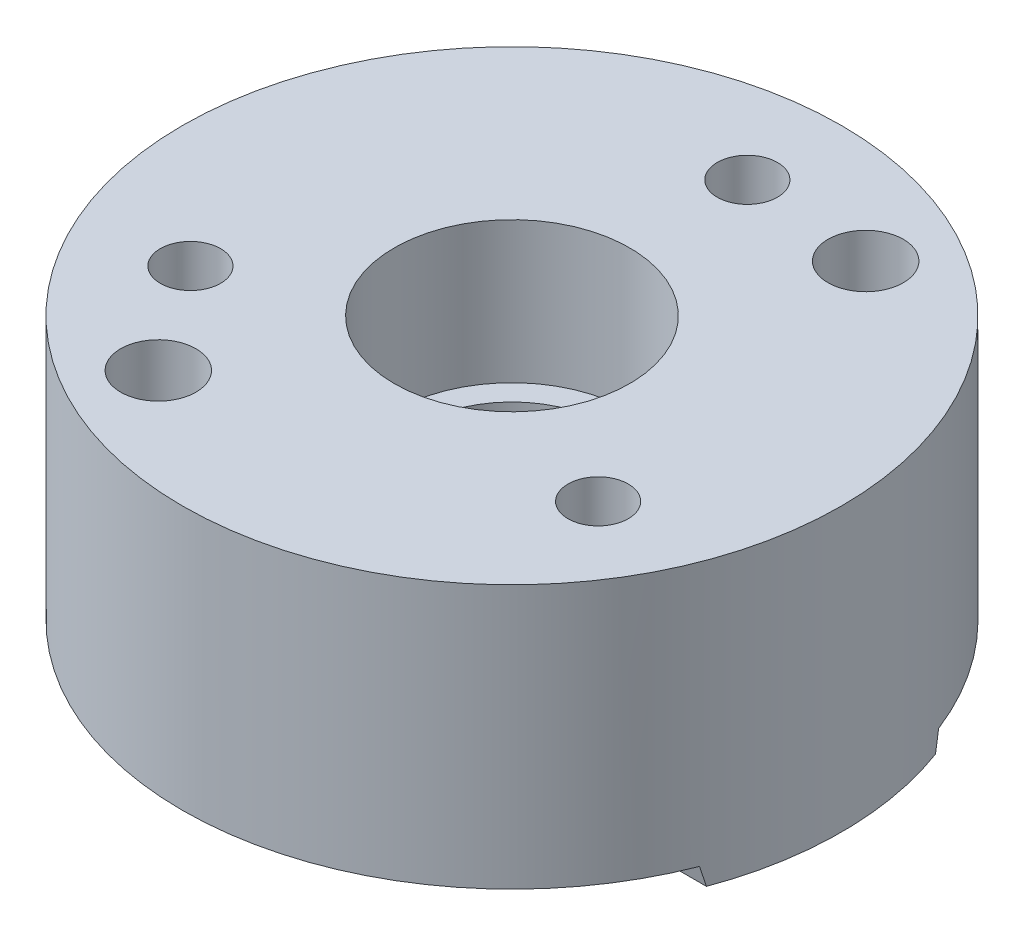
SolidWorks part; units mm, degrees
material "K110"
ref_plane "Front Plane" through (0, 0, 0) normal (0, 0, 1) x (1, 0, 0)
ref_plane "Top Plane" through (0, 0, 0) normal (0, 1, 0) x (1, 0, 0)
ref_plane "Right Plane" through (0, 0, 0) normal (1, 0, 0) x (0, 0, -1)
sketch "Sketch1" plane through (0, 0, 0) normal (0, 1, 0) x (1, 0, 0)
  circle A0 centre (0, 0) radius 35
  circle A1 centre (0, 0) radius 10
  dimension "D1" = 20
  dimension "D2" = 70
extrude "Boss-Extrude1" add sketch "Sketch1" against normal blind 30
sketch "Sketch4" plane through (0, 0, 0) normal (0, 1, 0) x (1, 0, 0)
  circle A0 centre (0, 0) radius 12.5
  dimension "D1" = 25
extrude "Cut-Extrude2" cut sketch "Sketch4" against normal blind 15
hole_wizard "CBORE for M6 Hex Socket Head Cap Screw1" positions "Sketch15" profile "Sketch8" counterbore size "M6" standard "ISO" end condition through all
sketch "Sketch15" plane through (0, -30, 0) normal (0, -1, 0) x (-1, 0, 0)
  line L0 (0, 25) -> (0, 0) construction
  line L1 (0, 0) -> (-21.6506, -12.5) construction
  line L3 (0, 0) -> (21.6506, -12.5) construction
  circle A0 centre (0, 0) radius 25 construction
  point P0 (0, 25)
  point P2 (21.6506, -12.5)
  point P4 (-21.6506, -12.5)
  dimension "D1" = 50
  dimension "D2" = 120
  dimension "D3" = 120
sketch "Sketch8" plane through (0, -30, -25) normal (1, 0, 0) x (0, 0, -1)
  line L0 (0, 0) -> (0, 30)
  line L1 (0, 30) -> (3.2, 30)
  line L3 (3.2, 30) -> (3.2, 8.4)
  line L4 (3.2, 8.4) -> (5.5, 8.4)
  line L5 (5.5, 8.4) -> (5.5, 0)
  line L7 (5.5, 0) -> (0, 0)
  line L11 (0, -6.35) -> (0, 107.95) construction
  dimension "Thru Hole Dia." = 6.4
  dimension "Thru Hole Depth" = 30
  dimension "C'Bore Dia." = 11
  dimension "C'Bore Depth" = 8.4
hole_wizard "Ø8.0mm Dowel Hole1" positions "Sketch17" profile "Sketch12" hole size "Ø8.0" standard "ISO" end condition through all
sketch "Sketch17" plane through (0, -30, 0) normal (0, -1, 0) x (-1, 0, 0)
  line L0 (-13.75, 23.8157) -> (13.75, -23.8157) construction
  line L1 (0, 35) -> (0, -35) construction
  circle A0 centre (0, 0) radius 27.5 construction
  circle A1 centre (0, 0) radius 35 construction
  point P0 (13.75, -23.8157)
  point P2 (-13.75, 23.8157)
  point P26 (0, 0)
  dimension "D1" = 55
  dimension "D2" = 30
sketch "Sketch12" plane through (-13.75, -30, 23.8157) normal (1, 0, 0) x (0, 0, -1)
  line L0 (0, 0) -> (0, 30)
  line L1 (0, 30) -> (4, 30)
  line L2 (4, 30) -> (4, 0)
  line L5 (4, 0) -> (0, 0)
  line L11 (0, -6.35) -> (0, 107.95) construction
  dimension "Thru Hole Dia." = 8
  dimension "Thru Hole Depth" = 30
sketch "Sketch14" plane through (0, -30, 0) normal (0, -1, 0) x (1, 0, 0)
  line L0 (-58.6405, -12.7) -> (-12.0399, -12.7) construction
  line L1 (-35, 12.7) -> (35, 12.7)
  line L2 (-35, 12.7) -> (-35, -12.7)
  line L3 (-35, -12.7) -> (35, -12.7)
  line L4 (35, 12.7) -> (35, -12.7)
  line L5 (-35, 12.7) -> (35, -12.7) construction
  line L6 (-35, -12.7) -> (35, 12.7) construction
  circle A0 centre (0, 0) radius 35 construction
  point P0 (0, 0)
extrude "Cut-Extrude3" cut sketch "Sketch14" against normal blind 2 flip side to cut
sketch "Sketch16" plane through (0, -30, 0) normal (0, -1, 0) x (1, 0, 0)
  circle A0 centre (22.5, 0) radius 4.25
  dimension "D1" = 8.5
sketch "Sketch18" plane through (0, -30, 0) normal (0, -1, 0) x (1, 0, 0)
  circle A1 centre (-13.665, 0) radius 2.1
  dimension "D1" = 4.2
extrude "Cut-Extrude5" cut sketch "Sketch18" against normal blind 3
sketch "Sketch19" plane through (0, 0, 0) normal (1, 0, 0) x (0, 0, -1)
  line L2 (-12.7, -28) -> (-12.1641, -30)
  line L3 (-12.7, -30) -> (12.7, -30) construction
  line L4 (-12.1641, -30) -> (-12.7, -30)
  line L5 (-12.7, -30) -> (-12.7, -28)
  line L6 (12.7, -28) -> (12.1641, -30)
  line L7 (12.1641, -30) -> (12.7, -30)
  line L8 (12.7, -30) -> (12.7, -28)
  dimension "D1" = 15
  dimension "D2" = 15
extrude "Cut-Extrude6" cut sketch "Sketch19" against normal through all both and the other way through all
sketch "Sketch20" plane through (0, -30, 0) normal (0, -1, 0) x (1, 0, 0)
  line L0 (-16.1609, 12.1641) -> (16.1609, 12.1641) construction
  line L1 (-12.5811, 12.1641) -> (12.5811, 12.1641)
  line L2 (-32.8182, -12.1641) -> (32.8182, -12.1641) construction
  line L3 (-12.5811, -12.1641) -> (12.5811, -12.1641)
  arc A0 (12.5811, 12.1641) -> (-12.5811, 12.1641) centre (0, 0) ccw
  arc A1 (-12.5811, -12.1641) -> (12.5811, -12.1641) centre (0, 0) ccw
  dimension "D1" = 35
extrude "Boss-Extrude2" add sketch "Sketch20" against normal up to surface (2 mm away) up to face at (13.75, -28, -27.8157)
draft "Draft1" type of draft neutral plane draft angle 3 faces to draft 1 face at (0, -28.9945, -14.9675) neutral plane through (0, -28, 0) neutral plane normal (0, -1, 0) parameters "D1"=3
